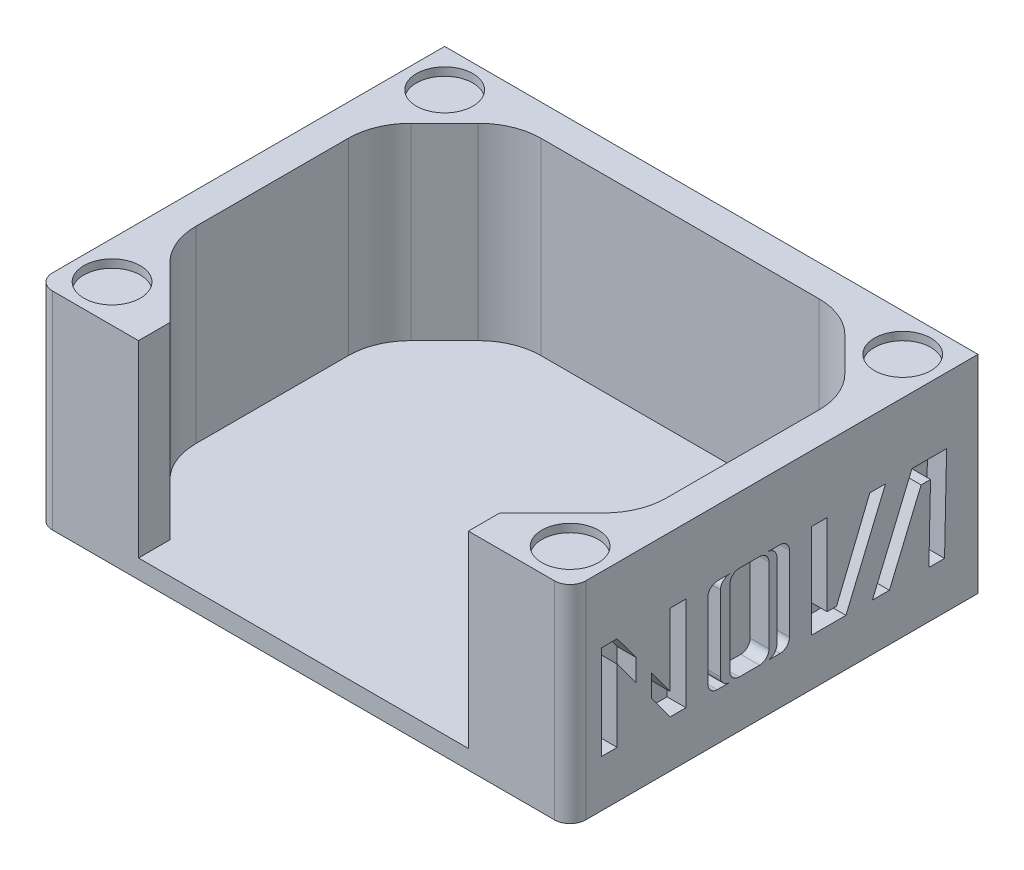
SolidWorks part; units mm, degrees
other "Markup1"
sketch "Sketch4" plane through (-85, 66, -65) normal (0, 1, 0) x (1, 0, 0)
ref_plane "Front Plane" through (0, 0, 0) normal (0, 0, 1) x (1, 0, 0)
ref_plane "Top Plane" through (0, 0, 0) normal (0, 1, 0) x (1, 0, 0)
ref_plane "Right Plane" through (0, 0, 0) normal (1, 0, 0) x (0, 0, -1)
sketch "Sketch1" plane through (0, 0, 0) normal (0, 1, 0) x (1, 0, 0)
  line L1 (-85, -65) -> (85, -65)
  line L2 (-85, -65) -> (-85, 65)
  line L3 (-85, 65) -> (85, 65)
  line L4 (85, -65) -> (85, 65)
  line L5 (-85, -65) -> (85, 65) construction
  line L6 (-85, 65) -> (85, -65) construction
  point P0 (0, 0)
  dimension "D1" = 170
  dimension "D2" = 130
extrude "Boss-Extrude1" add sketch "Sketch1" along normal blind 6
sketch "Sketch2" plane through (0, 6, 0) normal (0, 1, 0) x (1, 0, 0)
  line L10 (-75, -32.5736) -> (-75, 0)
  line L39 (-85, -65) -> (-85, 0)
  line L40 (-85, 65) -> (-85, -65) construction
  line L43 (-85, 0) -> (-75, 0)
  line L45 (75, 0) -> (85, 0)
  line L48 (45, -55) -> (-45, -55)
  line L49 (75, -32.5736) -> (75, 0)
  line L50 (85, 0) -> (85, -65)
  line L51 (85, -65) -> (85, 65) construction
  line L52 (85, -65) -> (-85, -65)
  line L53 (-85, -65) -> (85, -65) construction
  line L62 (-52.5736, -55) -> (-45, -55)
  line L67 (52.5736, -55) -> (45, -55)
  line L68 (-75, -32.5736) -> (-52.5736, -55)
  line L69 (52.5736, -55) -> (75, -32.5736)
  point P2 (-63.7868, -43.7868)
  point P3 (63.7868, -43.7868)
  dimension "D2" = 30
  dimension "D3" = 30
  dimension "D4" = 10
  dimension "D13" = 10
  dimension "D14" = 10
extrude "Boss-Extrude2" add sketch "Sketch2" along normal blind 60
mirror "Mirror1" about plane through (0, 0, 0) normal (0, 0, 1) of "Boss-Extrude2"
sketch "Sketch3" plane through (0, 66, 0) normal (0, 1, 0) x (1, 0, 0)
  line L0 (-85, 65) -> (85, 65) construction
  line L1 (-85, 65) -> (-85, -65) construction
  circle A0 centre (-73, 53) radius 9
  dimension "D1" = 18
  dimension "D2" = 12
  dimension "D3" = 12
extrude "Cut-Extrude1" cut sketch "Sketch3" against normal blind 2.6
fillet "Fillet1" radius 20 6 edges at (-52.5736, 36, -55) (-75, 36, -32.5736) (-75, 36, 32.5736) (75, 36, -32.5736) (52.5736, 36, -55) (75, 36, 32.5736)
mirror "Mirror2" about plane through (0, 0, 0) normal (1, 0, 0) of "Cut-Extrude1"
mirror "Mirror3" about plane through (0, 0, 0) normal (0, 0, 1) of "Mirror2", "Cut-Extrude1"
sketch "Sketch5" plane through (0, 66, 0) normal (0, 1, 0) x (1, 0, 0)
  line L0 (-52.5736, -55) -> (-52.5736, -65)
  line L1 (-85, -65) -> (85, -65) construction
  line L2 (-52.5736, -55) -> (52.5736, -55)
  line L3 (52.5736, -55) -> (52.5736, -65)
  line L4 (52.5736, -65) -> (-52.5736, -65)
extrude "Cut-Extrude2" cut sketch "Sketch5" against normal blind 60
sketch "Sketch7" plane through (85, 0, 0) normal (1, 0, 0) x (0, 0, -1)
  line L0 (-55, 15) -> (-55, 45)
  line L1 (-55, 45) -> (-50, 45)
  line L2 (-50, 15) -> (-50, 38)
  line L3 (-50, 38) -> (-44, 29.8387)
  line L4 (-50, 45) -> (-44, 36.8387)
  line L5 (-33.091, 22) -> (-33.091, 45)
  line L6 (-28.091, 45) -> (-28.091, 15)
  line L7 (-28.091, 45) -> (-33.091, 45)
  line L8 (-33.091, 15) -> (-28.091, 15)
  line L9 (-55, 15) -> (-50, 15)
  line L10 (-65, 0) -> (65, 0) construction
  line L11 (-65, 66) -> (65, 66) construction
  line L12 (-65, 66) -> (-65, 0) construction
  line L13 (1.909, 45) -> (-2.091, 45)
  line L14 (4.909, 42) -> (4.909, 18)
  line L15 (1.909, 15) -> (-2.091, 15)
  line L16 (-21.091, 42) -> (-21.091, 18)
  line L18 (0.909, 42) -> (0.909, 18)
  line L20 (-17.091, 42) -> (-17.091, 18)
  line L21 (11.909, 45) -> (11.909, 15)
  line L22 (11.909, 15) -> (22.909, 15)
  line L23 (22.909, 15) -> (35.5168, 45)
  line L24 (35.5168, 45) -> (30.5168, 45)
  line L27 (16.909, 45) -> (11.909, 45)
  line L30 (19.909, 19) -> (30.5168, 45)
  line L31 (16.909, 45) -> (16.909, 19)
  line L32 (16.909, 19) -> (19.909, 19)
  line L33 (31.3478, 15) -> (43.9555, 45)
  line L34 (43.9555, 45) -> (55, 45)
  line L35 (55, 45) -> (54.3407, 15)
  line L36 (54.3407, 15) -> (49.3395, 15)
  line L37 (49.3395, 15) -> (49.8675, 39.0236)
  line L38 (49.8675, 39.0236) -> (46.8675, 39.0236)
  line L39 (46.8675, 39.0236) -> (36.7714, 15)
  line L40 (36.7714, 15) -> (31.3478, 15)
  line L41 (-14.091, 45) -> (-18.091, 45)
  line L42 (65, 66) -> (65, 0) construction
  line L43 (-14.091, 15) -> (-18.091, 15)
  line L44 (-44, 36.8387) -> (-44, 29.8387)
  line L45 (-4.6248, 15) -> (-11.091, 15)
  line L46 (-1.6248, 18) -> (-1.6248, 42)
  line L47 (-4.6248, 45) -> (-11.091, 45)
  line L48 (-14.091, 18) -> (-14.091, 42)
  line L49 (-1.6248, 15) -> (-14.091, 45) construction
  line L50 (-1.6248, 45) -> (-14.091, 15) construction
  line L51 (-39.091, 30.1613) -> (-39.091, 23.1613)
  line L52 (-39.091, 23.1613) -> (-33.091, 15)
  line L53 (-39.091, 30.1613) -> (-33.091, 22)
  arc A0 (4.909, 18) -> (1.909, 15) centre (1.909, 18) cw
  arc A1 (1.909, 45) -> (4.909, 42) centre (1.909, 42) cw
  arc A2 (-18.091, 45) -> (-21.091, 42) centre (-18.091, 42) ccw
  arc A3 (-18.091, 15) -> (-21.091, 18) centre (-18.091, 18) cw
  arc A4 (-14.091, 15) -> (-17.091, 18) centre (-14.091, 18) cw
  arc A5 (0.909, 18) -> (-2.091, 15) centre (-2.091, 18) cw
  arc A6 (-2.091, 45) -> (0.909, 42) centre (-2.091, 42) cw
  arc A7 (-14.091, 45) -> (-17.091, 42) centre (-14.091, 42) ccw
  arc A8 (-11.091, 15) -> (-14.091, 18) centre (-11.091, 18) cw
  arc A9 (-4.6248, 15) -> (-1.6248, 18) centre (-4.6248, 18) ccw
  arc A10 (-1.6248, 42) -> (-4.6248, 45) centre (-4.6248, 42) ccw
  arc A11 (-11.091, 45) -> (-14.091, 42) centre (-11.091, 42) ccw
  point P49 (-7.8579, 30)
  dimension "D12" = 3
  dimension "D8" = 3
  dimension "D1" = 5
  dimension "D2" = 5
  dimension "D3" = 7
  dimension "D4" = 7
  dimension "D5" = 30
  dimension "D6" = 15
  dimension "D7" = 21
  dimension "D9" = 4
  dimension "D10" = 4
  dimension "D11" = 6
  dimension "D13" = 23
  dimension "D14" = 28.5467
  dimension "D15" = 28.5467
  dimension "D16" = 30
  dimension "D17" = 23
  dimension "D18" = 4.1463
  dimension "D19" = 10
  dimension "D20" = 7
  dimension "D21" = 18
  dimension "D22" = 26
  dimension "D23" = 30
  dimension "D24" = 3
  dimension "D25" = 11
  dimension "D26" = 5
  dimension "D27" = 7
  dimension "D28" = 5
  dimension "D29" = 5
  dimension "D30" = 5
  dimension "D31" = 5
  dimension "D32" = 0.6
  dimension "D33" = 5
  dimension "D34" = 10
  dimension "D35" = 3
  dimension "D36" = 6
extrude "Cut-Extrude3" cut sketch "Sketch7" against normal blind 6
fillet "Fillet2" radius 5 2 edges at (-85, 33, 65) (85, 33, 65)
sketch "Sketch12" plane through (-85, 0, 0) normal (-1, 0, 0) x (0, 0, 1)
  line L0 (-39, 47) -> (-35, 47)
  line L1 (-35, 47) -> (-30.4827, 31.2383)
  line L2 (-30.4827, 31.2383) -> (-23.8857, 47)
  line L3 (-23.8857, 47) -> (-19.5992, 47)
  line L4 (-19.5992, 47) -> (-32.1555, 17)
  line L5 (-32.1555, 17) -> (-36.4918, 17)
  line L6 (-36.4918, 17) -> (-33, 25.3426)
  line L7 (-33, 25.3426) -> (-39, 47)
  line L8 (-14.5992, 47) -> (-27.1555, 17)
  line L9 (-14.5992, 47) -> (-4.2102, 47)
  line L10 (-4.2102, 47) -> (-4.2102, 17)
  line L11 (-4.2102, 17) -> (-8.2102, 17)
  line L12 (-8.2102, 17) -> (-8.2102, 43.7918)
  line L13 (-8.2102, 43.7918) -> (-12.2102, 43.7918)
  line L14 (-12.2102, 43.7918) -> (-23.1555, 17)
  line L15 (-23.1555, 17) -> (-27.1555, 17)
  line L16 (-37, 25.3426) -> (-43, 47)
  line L17 (-43, 47) -> (-47, 47)
  line L18 (-47, 47) -> (-41, 25.3426)
  line L19 (-41, 25.3426) -> (-44.4918, 17)
  line L20 (-44.4918, 17) -> (-40.4918, 17)
  line L21 (-40.4918, 17) -> (-37, 25.3426)
  line L22 (0.7898, 47) -> (0.7898, 17)
  line L23 (0.7898, 17) -> (4.7898, 17)
  line L24 (4.7898, 17) -> (4.7898, 30)
  line L25 (4.7898, 30) -> (13.888, 30)
  line L26 (13.888, 30) -> (13.888, 34)
  line L27 (13.888, 34) -> (4.7898, 34)
  line L28 (4.7898, 34) -> (4.7898, 43)
  line L29 (4.7898, 43) -> (13.888, 43)
  line L30 (13.888, 43) -> (13.888, 47)
  line L31 (13.888, 47) -> (0.7898, 47)
  line L32 (-65, 66) -> (60, 66) construction
  line L35 (20.272, 47) -> (24.272, 47)
  line L37 (20.272, 17) -> (24.272, 17)
  line L38 (42, 47) -> (42, 43)
  line L39 (38, 47) -> (31.136, 36.9332)
  line L41 (24.272, 17) -> (31.136, 27.0668)
  line L45 (20.272, 43) -> (27.7723, 32)
  line L47 (42, 21) -> (34.4997, 32)
  line L48 (-65, 66) -> (-65, 0) construction
  line L49 (60, 0) -> (60, 66) construction
  line L50 (38, 47) -> (42, 47)
  line L51 (31.136, 27.0668) -> (38, 17)
  line L52 (27.7723, 32) -> (20.272, 21)
  line L53 (31.136, 36.9332) -> (24.272, 47)
  line L54 (34.4997, 32) -> (42, 43)
  line L56 (38, 17) -> (42, 17)
  line L57 (42, 21) -> (42, 17)
  line L61 (20.272, 43) -> (20.272, 47)
  line L62 (20.272, 21) -> (12.2453, 21)
  line L63 (12.2453, 21) -> (12.2453, 17)
  line L64 (12.2453, 17) -> (20.272, 17)
  dimension "D1" = 4
  dimension "D2" = 5
  dimension "D3" = 4
  dimension "D4" = 4
  dimension "D5" = 4
  dimension "D6" = 3.2082
  dimension "D7" = 4
  dimension "D8" = 4
  dimension "D9" = 5
  dimension "D10" = 4
  dimension "D11" = 4
  dimension "D12" = 10
  dimension "D13" = 4
  dimension "D14" = 4
  dimension "D15" = 30
  dimension "D16" = 4
  dimension "D17" = 4
  dimension "D18" = 4
  dimension "D19" = 9
  dimension "D20" = 4
  dimension "D21" = 4
  dimension "D22" = 19
  dimension "D23" = 4
  dimension "D24" = 4
  dimension "D25" = 4
  dimension "D26" = 4
  dimension "D27" = 4
  dimension "D28" = 4
  dimension "D29" = 4
  dimension "D30" = 4
  dimension "D31" = 18
  dimension "D32" = 18
extrude "Cut-Extrude6" cut sketch "Sketch12" against normal blind 6
